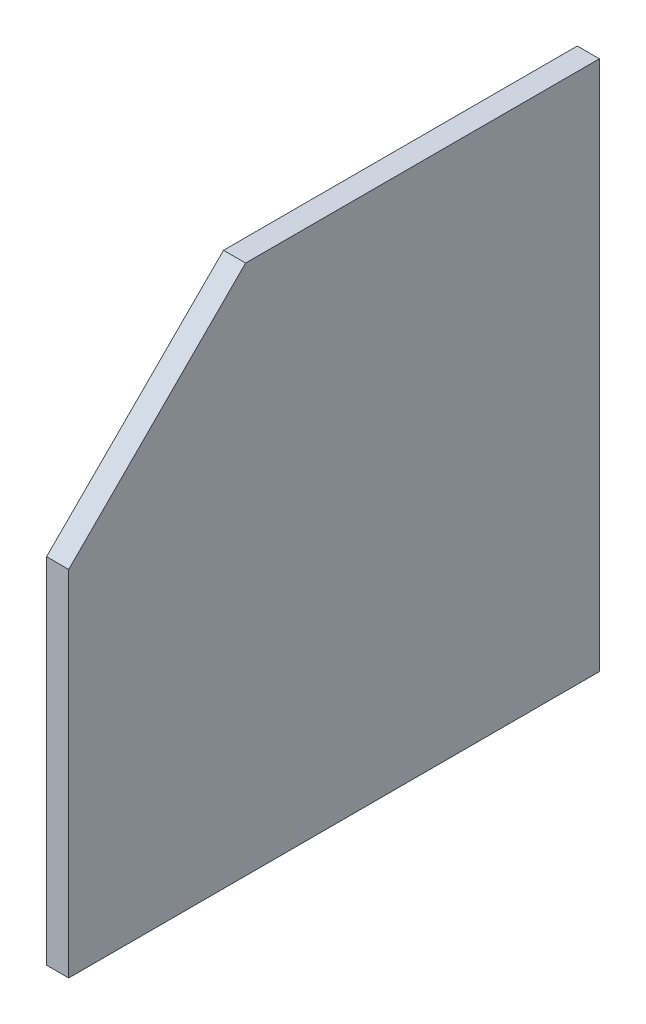
SolidWorks part; units mm, degrees
ref_plane "Front" through (0, 0, 0) normal (0, 0, 1) x (1, 0, 0)
ref_plane "Top" through (0, 0, 0) normal (0, 1, 0) x (1, 0, 0)
ref_plane "Right" through (0, 0, 0) normal (1, 0, 0) x (0, 0, -1)
sketch "Sketch1" plane through (0, 0, 0) normal (1, 0, 0) x (0, 0, -1)
  line L0 (38.1, 38.1) -> (-12.7, 38.1)
  line L1 (38.1, -38.1) -> (-38.1, -38.1)
  line L2 (38.1, -38.1) -> (38.1, 38.1)
  line L3 (38.1, 38.1) -> (-38.1, 38.1) construction
  line L4 (-38.1, -38.1) -> (-38.1, 38.1) construction
  line L5 (38.1, -38.1) -> (-38.1, 38.1) construction
  line L6 (38.1, 38.1) -> (-38.1, -38.1) construction
  line L7 (-12.7, 38.1) -> (-38.1, 12.7)
  line L8 (-38.1, 12.7) -> (-38.1, -38.1)
  point P0 (0, 0)
  dimension "D1" = 76.2
  dimension "D2" = 50.8
extrude "Boss-Extrude1" add sketch "Sketch1" along normal blind 3.175
